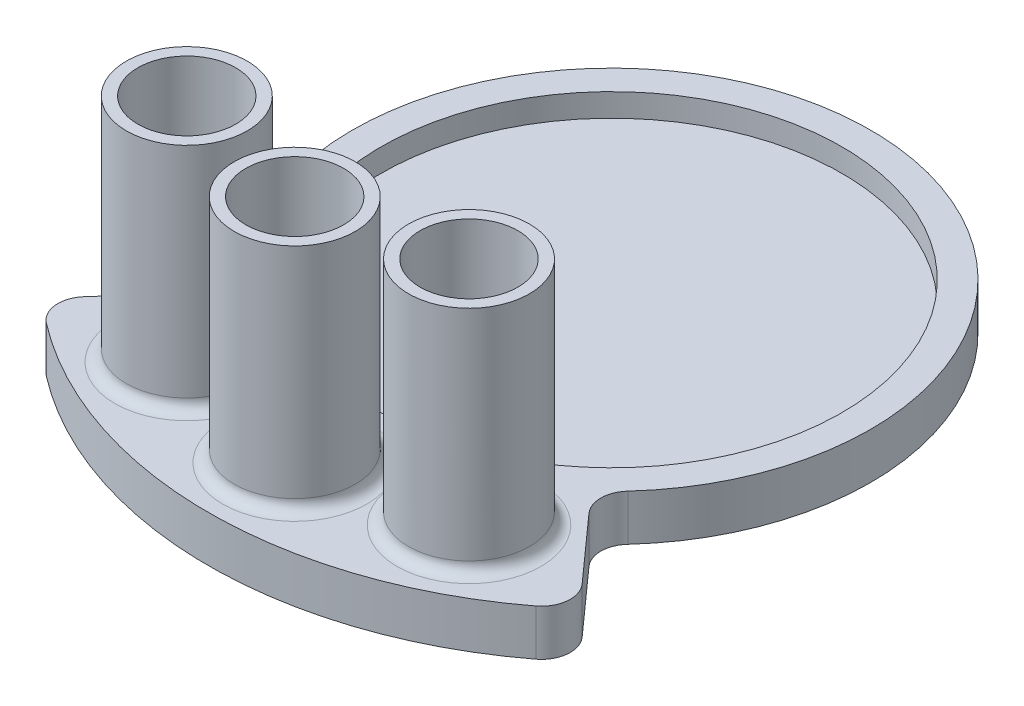
SolidWorks part; units mm, degrees
ref_plane "Plan de face" through (0, 0, 0) normal (0, 0, 1) x (1, 0, 0)
ref_plane "Plan de dessus" through (0, 0, 0) normal (0, 1, 0) x (1, 0, 0)
ref_plane "Plan de droite" through (0, 0, 0) normal (1, 0, 0) x (0, 0, -1)
sketch "Esquisse1" plane through (0, 0, 0) normal (0, 1, 0) x (1, 0, 0)
  line L0 (0, -75.9934) -> (0, -123.4206) construction
  line L1 (-30, -33.541) -> (-46.6667, -52.1749)
  line L2 (30, -33.541) -> (46.6667, -52.1749)
  arc A0 (30, -33.541) -> (-30, -33.541) centre (0, 0) ccw
  arc A1 (-46.6667, -52.1749) -> (46.6667, -52.1749) centre (0, 0) ccw
  circle A2 centre (0, 0) radius 70 construction
  circle A3 centre (0, 0) radius 45 construction
  point P9 (0, 0)
  point P10 (0, 0)
  dimension "D1" = 90
  dimension "D3" = 30
  dimension "D2" = 25
extrude "Boss.-Extru.1" add sketch "Esquisse1" along normal blind 8
sketch "Esquisse2" plane through (0, 8, 0) normal (0, 1, 0) x (1, 0, 0)
  circle A0 centre (0, 0) radius 40
  dimension "D1" = 80
extrude "Enlèv. mat.-Extru.1" cut sketch "Esquisse2" against normal blind 4
sketch "Esquisse4" plane through (0, 8, 0) normal (0, 1, 0) x (1, 0, 0)
  line L0 (0, 13.6915) -> (0, -15.4088) construction
  circle A0 centre (0, -55) radius 10.5
  circle A2 centre (-24.5, -49.2418) radius 10.5
  circle A3 centre (0, 0) radius 55
  circle A4 centre (0, 0) radius 55 construction
  circle A5 centre (24.5, -49.2418) radius 10.5
  point P7 (0, 0)
  point P8 (0, -53.2079)
  point P9 (0, 0)
  point P10 (0, 0)
  point P16 (0, 0)
  point P17 (0, 0)
  dimension "D1" = 21
  dimension "D2" = 21
  dimension "D4" = 24.5
  dimension "D3" = 15
extrude "Boss.-Extru.2" add sketch "Esquisse4" along normal blind 40
sketch "Esquisse5" plane through (0, 48, 0) normal (0, 1, 0) x (1, 0, 0)
  circle A0 centre (0, -55) radius 8.5
  circle A2 centre (-24.5, -49.2418) radius 8.5
  circle A3 centre (-24.5, -49.2418) radius 10.5 construction
  circle A4 centre (24.5, -49.2418) radius 8.5
  circle A5 centre (24.5, -49.2418) radius 10.5 construction
  point P5 (0, 0)
  point P10 (79.4145, -31.2082)
  dimension "D1" = 17
  dimension "D2" = 17
  dimension "D3" = 17
extrude "Enlèv. mat.-Extru.2" cut sketch "Esquisse5" against normal blind 40
fillet "Congé1" radius 5 4 edges at (46.6667, 4, 52.1749) (-46.6667, 4, 52.1749) (-30, 4, 33.541) (30, 4, 33.541)
fillet "Congé4" radius 2 3 edges at (24.5, 8, 38.7418) (0, 8, 65.5) (-24.5, 8, 59.7418)
